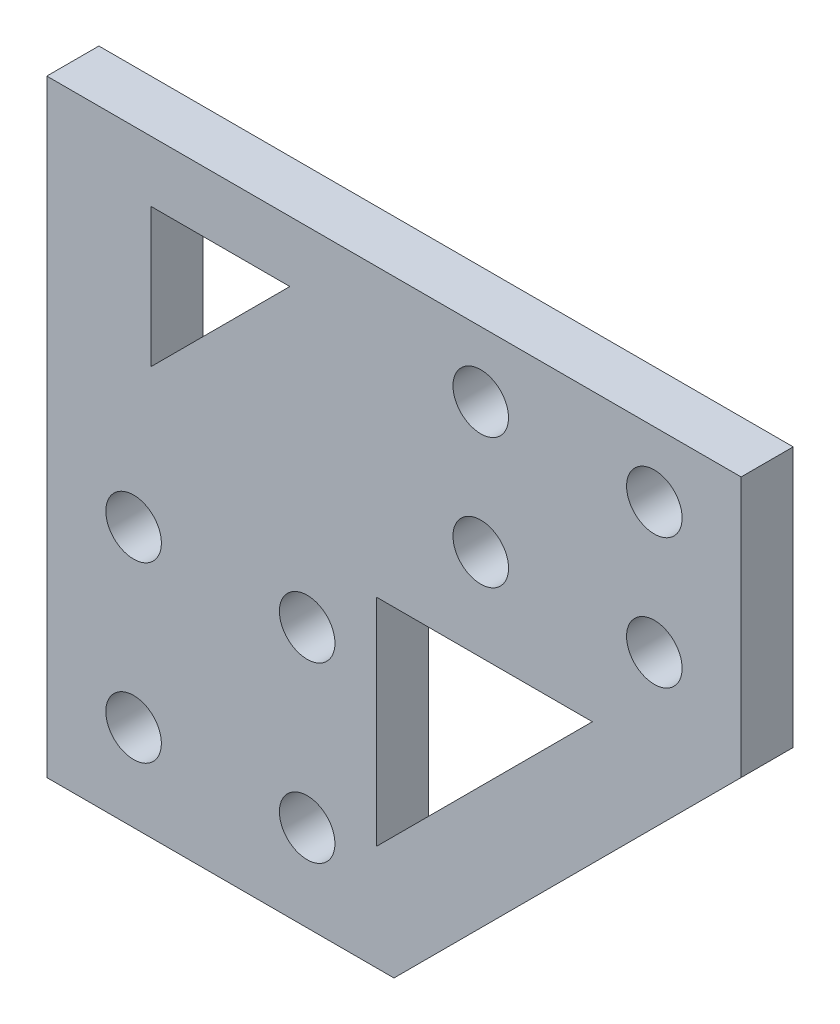
SolidWorks part; units mm, degrees
ref_plane "前视基准面" through (0, 0, 0) normal (0, 0, 1) x (1, 0, 0)
ref_plane "上视基准面" through (0, 0, 0) normal (0, 1, 0) x (1, 0, 0)
ref_plane "右视基准面" through (0, 0, 0) normal (1, 0, 0) x (0, 0, -1)
other "Configuration Table"
sketch "草图1" plane through (0, 0, 0) normal (0, 0, 1) x (1, 0, 0)
  line L0 (0, 0) -> (40, 0)
  line L1 (40, 0) -> (40, -15)
  line L2 (40, -15) -> (20, -35)
  line L3 (20, -35) -> (0, -35)
  line L4 (0, -35) -> (0, 0)
  line L5 (0, -25) -> (30, -25) construction
  line L6 (30, 0) -> (30, -25) construction
  line L7 (10, 0) -> (10, -35) construction
  line L8 (40, -7.5) -> (0, -7.5) construction
  line L9 (19, -16.5) -> (19, -28.9289)
  line L10 (19, -28.9289) -> (31.4289, -16.5)
  line L11 (31.4289, -16.5) -> (19, -16.5)
  line L12 (6, -3.5) -> (14, -3.5)
  line L13 (14, -3.5) -> (6, -11.5)
  line L14 (6, -3.5) -> (6, -11.5)
  circle A0 centre (5, -30) radius 1.6
  circle A1 centre (15, -30) radius 1.6
  circle A2 centre (15, -20) radius 1.6
  circle A3 centre (5, -20) radius 1.6
  circle A4 centre (35, -3.75) radius 1.6
  circle A5 centre (35, -11.25) radius 1.6
  circle A6 centre (25, -11.25) radius 1.6
  circle A7 centre (25, -3.75) radius 1.6
  point P34 (25.2145, -22.7145)
  dimension "D7" = 3.2
  dimension "D10" = 3.2
  dimension "D1" = 15
  dimension "D2" = 20
  dimension "D3" = 25
  dimension "D4" = 30
  dimension "D5" = 10
  dimension "D6" = 10
  dimension "D8" = 5
  dimension "D9" = 5
  dimension "D11" = 3.75
  dimension "D12" = 5
  dimension "D13" = 9
  dimension "D14" = 9
  dimension "D15" = 5
  dimension "D16" = 8
  dimension "D17" = 8
extrude "凸台-拉伸1" add sketch "草图1" along normal blind 3
